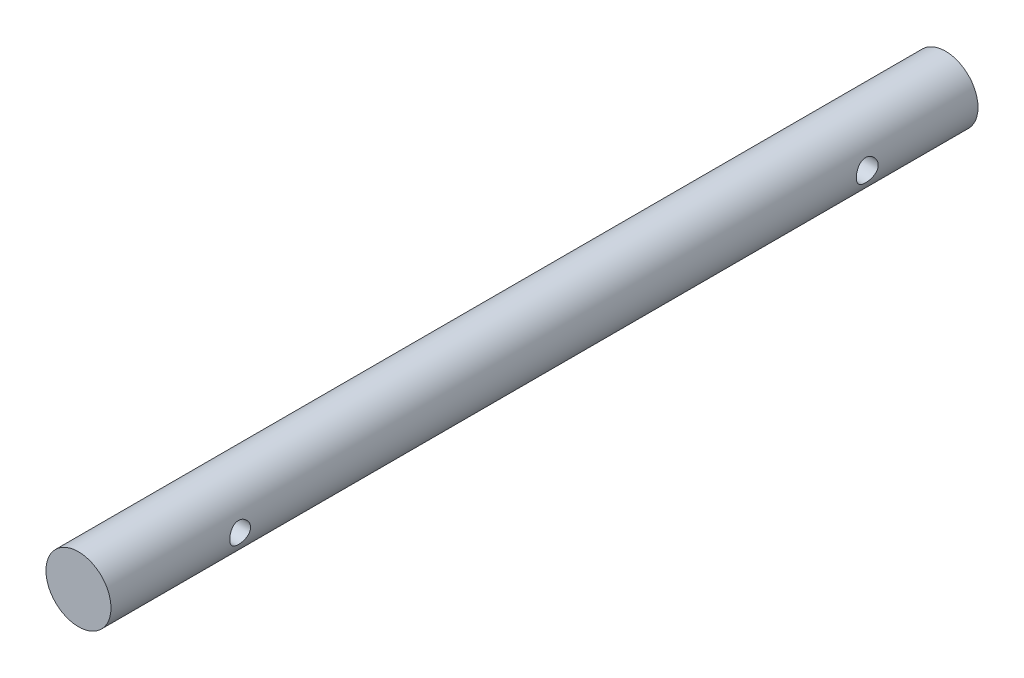
SolidWorks part; units mm, degrees
ref_plane "Front Plane" through (0, 0, 0) normal (0, 0, 1) x (1, 0, 0)
ref_plane "Top Plane" through (0, 0, 0) normal (0, 1, 0) x (1, 0, 0)
ref_plane "Right Plane" through (0, 0, 0) normal (1, 0, 0) x (0, 0, -1)
sketch "Sketch1" plane through (0, 0, 0) normal (0, 0, 1) x (1, 0, 0)
  circle A0 centre (0, 0) radius 2.3813
extrude "Boss-Extrude1" add sketch "Sketch1" along normal mid plane 63.5
sketch "Sketch4" plane through (0, 0, 0) normal (1, 0, 0) x (0, 0, -1)
  circle A0 centre (-22.2885, 0) radius 0.762
extrude "Cut-Extrude3" cut sketch "Sketch4" against normal through all and the other way through all
sketch "Sketch5" plane through (0, 0, 0) normal (1, 0, 0) x (0, 0, -1)
  circle A0 centre (23.6416, 0) radius 0.8001
extrude "Cut-Extrude4" cut sketch "Sketch5" against normal through all and the other way through all
